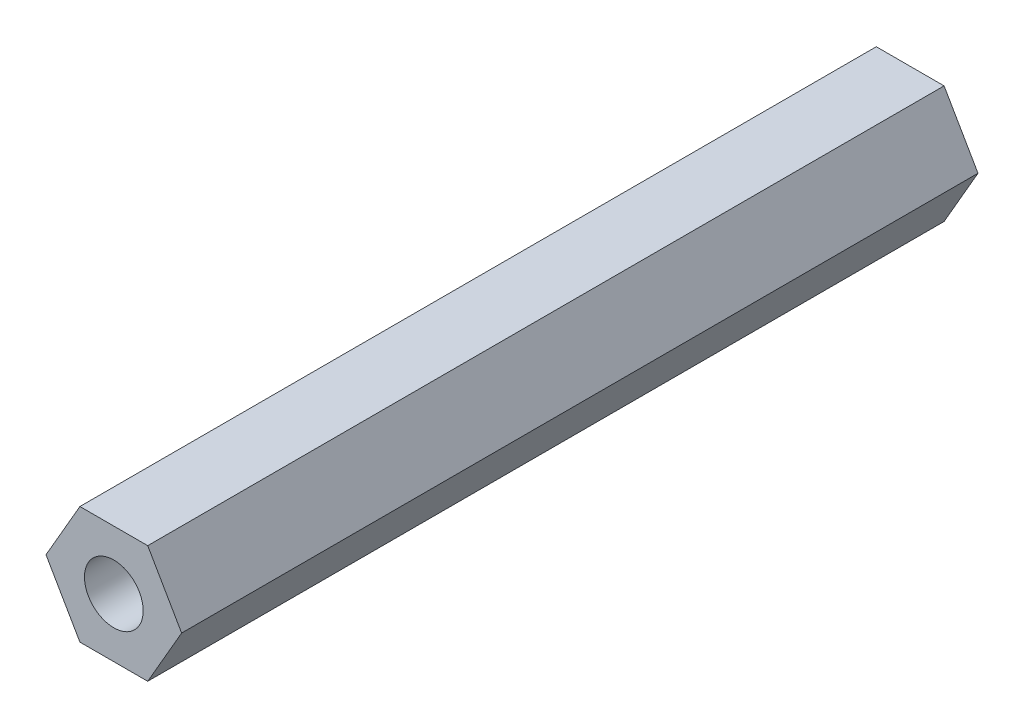
SolidWorks part; units mm, degrees
material "1060 Alloy"
ref_plane "Front Plane" through (0, 0, 0) normal (0, 0, 1) x (1, 0, 0)
ref_plane "Top Plane" through (0, 0, 0) normal (0, 1, 0) x (1, 0, 0)
ref_plane "Right Plane" through (0, 0, 0) normal (1, 0, 0) x (0, 0, -1)
sketch "Sketch1" plane through (0, 0, 0) normal (0, 0, 1) x (1, 0, 0)
  line L1 (3.6662, 6.35) -> (-3.6662, 6.35)
  line L2 (-3.6662, 6.35) -> (-7.3323, 0)
  line L3 (-7.3323, 0) -> (-3.6662, -6.35)
  line L4 (-3.6662, -6.35) -> (3.6662, -6.35)
  line L5 (3.6662, -6.35) -> (7.3323, 0)
  line L6 (7.3323, 0) -> (3.6662, 6.35)
  circle A0 centre (0, 0) radius 6.35 construction
  circle A1 centre (0, 0) radius 3.175
  dimension "D2" = 6.35
  dimension "D1" = 12.7
extrude "Boss-Extrude1" add sketch "Sketch1" along normal mid plane 86.106
